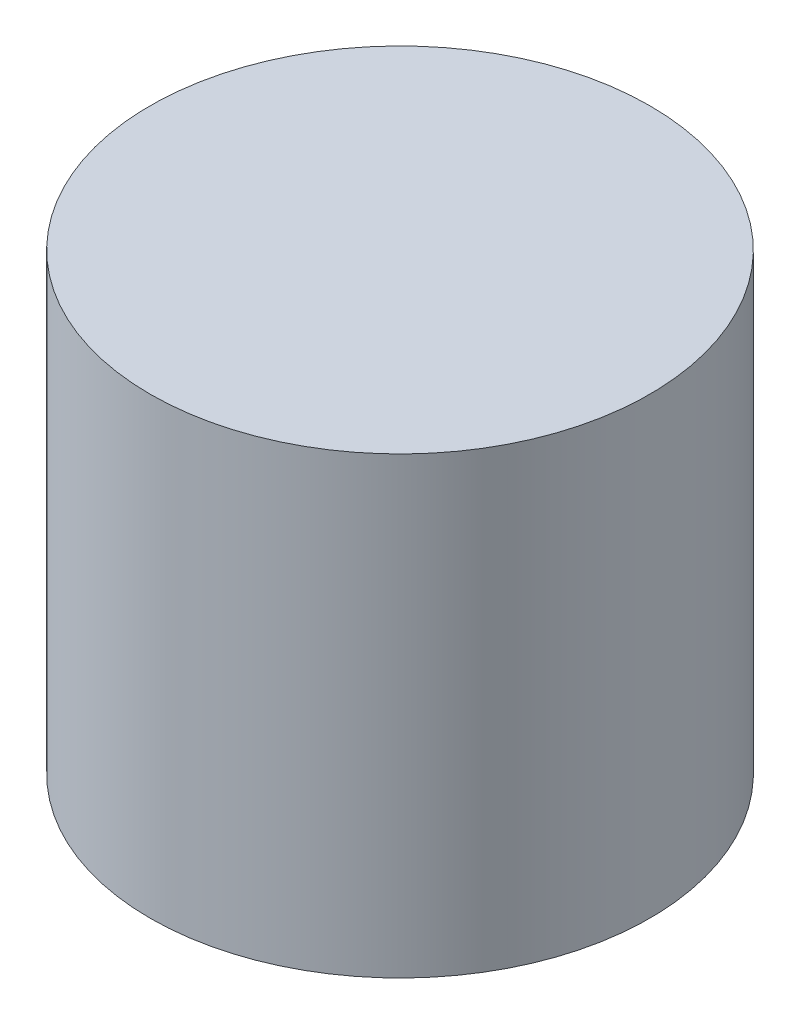
SolidWorks part; units mm, degrees
ref_plane "Front Plane" through (0, 0, 0) normal (0, 0, 1) x (1, 0, 0)
ref_plane "Top Plane" through (0, 0, 0) normal (0, 1, 0) x (1, 0, 0)
ref_plane "Right Plane" through (0, 0, 0) normal (1, 0, 0) x (0, 0, -1)
sketch "Sketch1" plane through (0, 0, 0) normal (0, 1, 0) x (1, 0, 0)
  circle A0 centre (0, 0) radius 41.9483
extrude "Boss-Extrude1" add sketch "Sketch1" along normal blind 76.2
